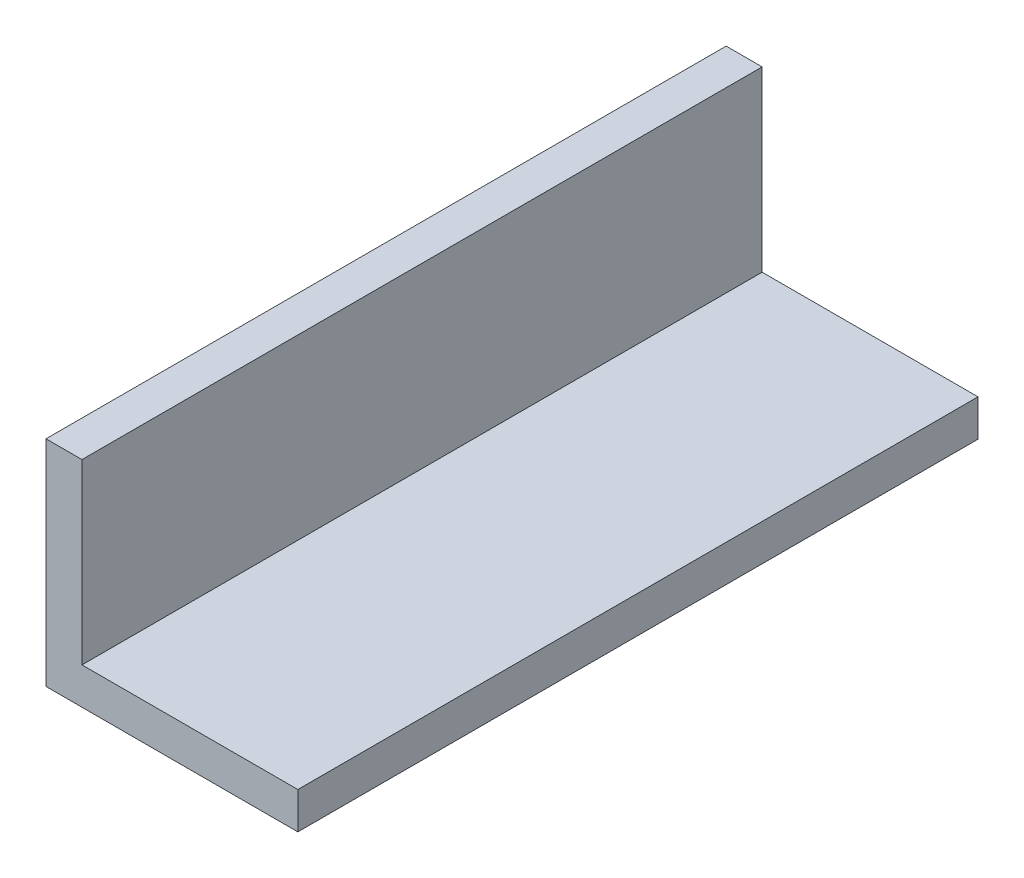
SolidWorks part; units mm, degrees
ref_plane "Plan de face" through (0, 0, 0) normal (0, 0, 1) x (1, 0, 0)
ref_plane "Plan de dessus" through (0, 0, 0) normal (0, 1, 0) x (1, 0, 0)
ref_plane "Plan de droite" through (0, 0, 0) normal (1, 0, 0) x (0, 0, -1)
sketch "Esquisse1" plane through (0, 0, 0) normal (0, 0, 1) x (1, 0, 0)
  line L0 (0, 0) -> (70.894, 0)
  line L1 (70.894, 0) -> (70.894, 10.3343)
  line L2 (70.894, 10.3343) -> (10.1332, 10.3343)
  line L3 (10.1332, 10.3343) -> (10.1332, 60.3873)
  line L4 (10.1332, 60.3873) -> (0, 60.3873)
  line L5 (0, 60.3873) -> (0, 0)
  dimension "D1" = 50.0529
  dimension "D2" = 60.7608
  dimension "D3" = 10.3343
extrude "Boss.-Extru.1" add sketch "Esquisse1" along normal blind 191.46
